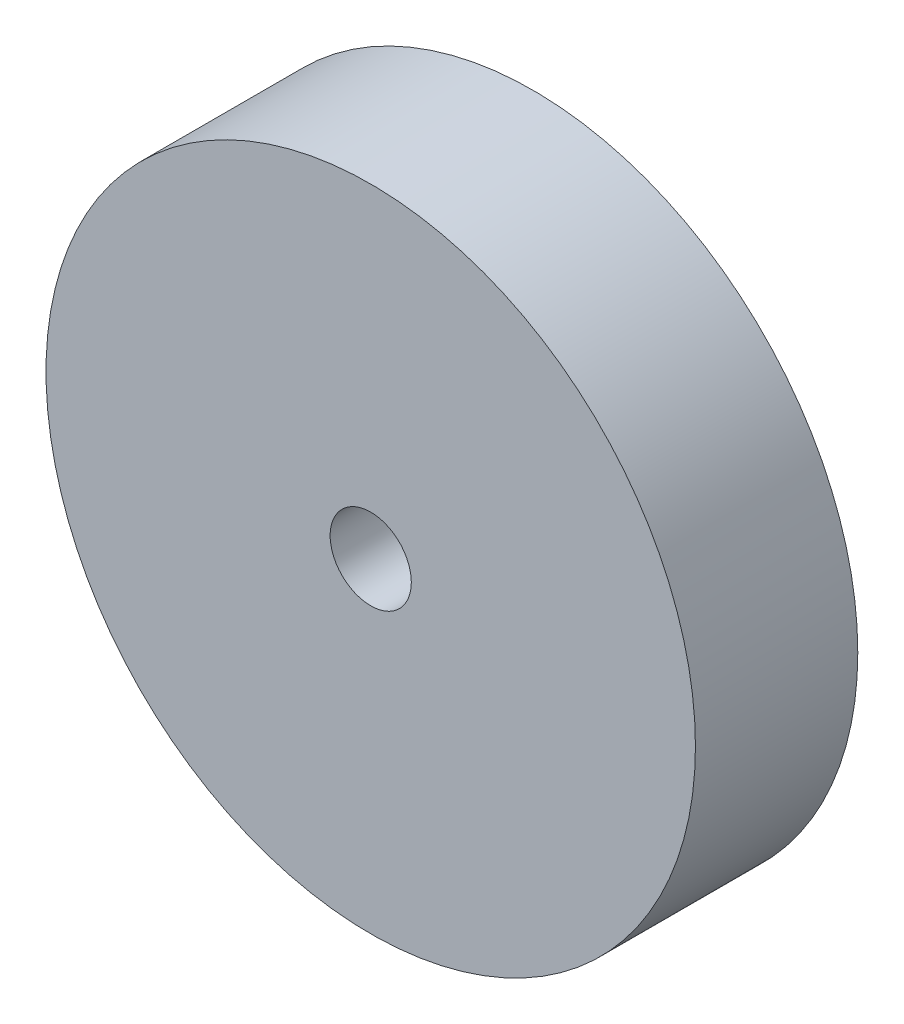
SolidWorks part; units mm, degrees
ref_plane "Front Plane" through (0, 0, 0) normal (0, 0, 1) x (1, 0, 0)
ref_plane "Top Plane" through (0, 0, 0) normal (0, 1, 0) x (1, 0, 0)
ref_plane "Right Plane" through (0, 0, 0) normal (1, 0, 0) x (0, 0, -1)
sketch "Sketch1" plane through (0, 0, 0) normal (0, 0, 1) x (1, 0, 0)
  circle A0 centre (0, 0) radius 20
  circle A1 centre (0, 0) radius 2.5
  dimension "D1" = 40
  dimension "D2" = 5
extrude "Boss-Extrude1" add sketch "Sketch1" along normal blind 10
